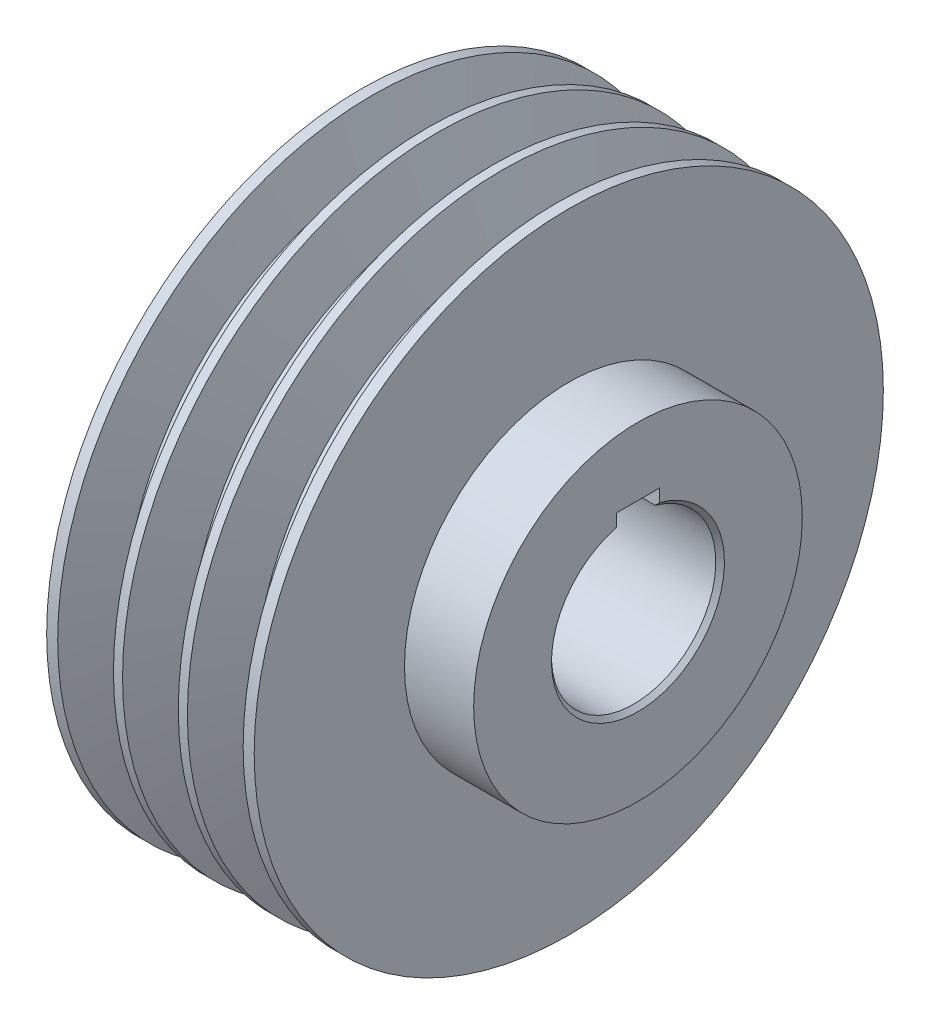
SolidWorks part; units mm, degrees
ref_plane "前视基准面" through (0, 0, 0) normal (0, 0, 1) x (1, 0, 0)
ref_plane "上视基准面" through (0, 0, 0) normal (0, 1, 0) x (1, 0, 0)
ref_plane "右视基准面" through (0, 0, 0) normal (1, 0, 0) x (0, 0, -1)
sketch "草图1" plane through (0, 0, 0) normal (0, 0, 1) x (1, 0, 0)
  line L0 (0, 0) -> (64.8368, 0) construction
  line L1 (0, 19) -> (0, 72.75)
  line L2 (0, 72.75) -> (48, 72.75)
  line L3 (48, 72.75) -> (48, 38)
  line L4 (48, 38) -> (64, 38)
  line L5 (64, 38) -> (64, 19)
  line L6 (64, 19) -> (0, 19)
  line L7 (2.5531, 72.75) -> (6.4957, 61.3) construction
  line L8 (6.4957, 61.3) -> (11.5043, 61.3) construction
  line L9 (11.5043, 61.3) -> (15.4469, 72.75) construction
  line L10 (0, 70) -> (48, 70) construction
  line L11 (9, 61.3) -> (9, 19) construction
  point P17 (3.5, 70)
  point P18 (14.5, 70)
  dimension "d2" = 145.5
  dimension "L" = 64
  dimension "B" = 48
  dimension "d" = 38
  dimension "d1" = 76
  dimension "dd" = 140
  dimension "f" = 9
  dimension "槽轮角" = 38
  dimension "bd" = 11
  dimension "hf" = 8.7
  dimension "ha" = 2.75
revolve "旋转1" add sketch "草图1" angle 360 about L0
sketch "草图2" plane through (0, 0, 0) normal (0, 0, 1) x (1, 0, 0)
  line L0 (11.5043, 61.3) -> (15.4469, 72.75) construction
  line L1 (6.4957, 61.3) -> (11.5043, 61.3) construction
  line L2 (2.5531, 72.75) -> (6.4957, 61.3) construction
  line L3 (11.5043, 61.3) -> (15.4469, 72.75)
  line L4 (6.4957, 61.3) -> (11.5043, 61.3)
  line L5 (2.5531, 72.75) -> (6.4957, 61.3)
  line L6 (2.5531, 72.75) -> (15.4469, 72.75)
  line L7 (0, 0) -> (48, 0) construction
  line L8 (48, -38) -> (48, 38) construction
revolve "切除-旋转1" cut sketch "草图2" angle 360 about L7
pattern_linear "阵列(线性)1" count 3 spacing 15 along (1, 0, 0) of "切除-旋转1"
chamfer "倒角1" distance 1 2 edges at (64, 0, 19) (0, 0, 19)
sketch "草图4" plane through (0, 0, 0) normal (-1, 0, 0) x (0, 0, 1)
  line L1 (-5, 18.3303) -> (5, 18.3303)
  line L2 (-5, 18.3303) -> (-5, 22.3)
  line L3 (-5, 22.3) -> (5, 22.3)
  line L4 (5, 18.3303) -> (5, 22.3)
  circle A0 centre (0, 0) radius 19 construction
  point P6 (1.7, 22.3)
  dimension "键槽高度" = 22.3
  dimension "键槽宽度" = 10
  dimension "t1" = 3.3
extrude "切除-拉伸1" cut sketch "草图4" against normal through all
